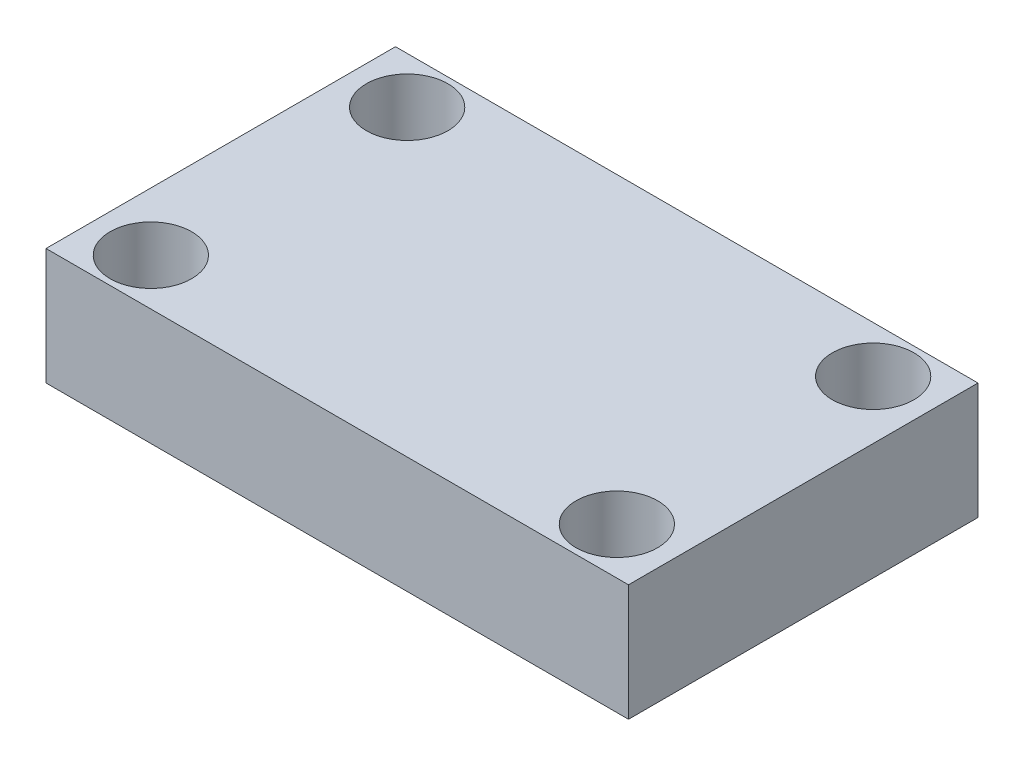
SolidWorks part; units mm, degrees
ref_plane "Front Plane" through (0, 0, 0) normal (0, 0, 1) x (1, 0, 0)
ref_plane "Top Plane" through (0, 0, 0) normal (0, 1, 0) x (1, 0, 0)
ref_plane "Right Plane" through (0, 0, 0) normal (1, 0, 0) x (0, 0, -1)
sketch "Sketch1" plane through (0, 0, 0) normal (0, 1, 0) x (1, 0, 0)
  line L1 (250, -150) -> (-250, -150)
  line L2 (250, -150) -> (250, 150)
  line L3 (250, 150) -> (-250, 150)
  line L4 (-250, -150) -> (-250, 150)
  line L5 (250, -150) -> (-250, 150) construction
  line L6 (250, 150) -> (-250, -150) construction
  point P0 (0, 0)
  dimension "D1" = 500
  dimension "D2" = 300
extrude "Boss-Extrude1" add sketch "Sketch1" along normal blind 100
sketch "Sketch2" plane through (0, 0, 0) normal (0, 1, 0) x (1, 0, 0)
  line L0 (250, 150) -> (-250, 150) construction
  line L1 (-250, 150) -> (-250, -150) construction
  line L3 (200, -110) -> (-200, -110) construction
  line L4 (200, -110) -> (200, 110) construction
  line L5 (200, 110) -> (-200, 110) construction
  line L6 (-200, -110) -> (-200, 110) construction
  line L7 (200, -110) -> (-200, 110) construction
  line L8 (200, 110) -> (-200, -110) construction
  circle A0 centre (-200, 110) radius 35
  circle A1 centre (200, 110) radius 35
  circle A2 centre (200, -110) radius 35
  circle A3 centre (-200, -110) radius 35
  point P6 (0, 0)
  dimension "D1" = 70
  dimension "D2" = 40
  dimension "D3" = 50
extrude "Cut-Extrude2" cut sketch "Sketch2" along normal through all
